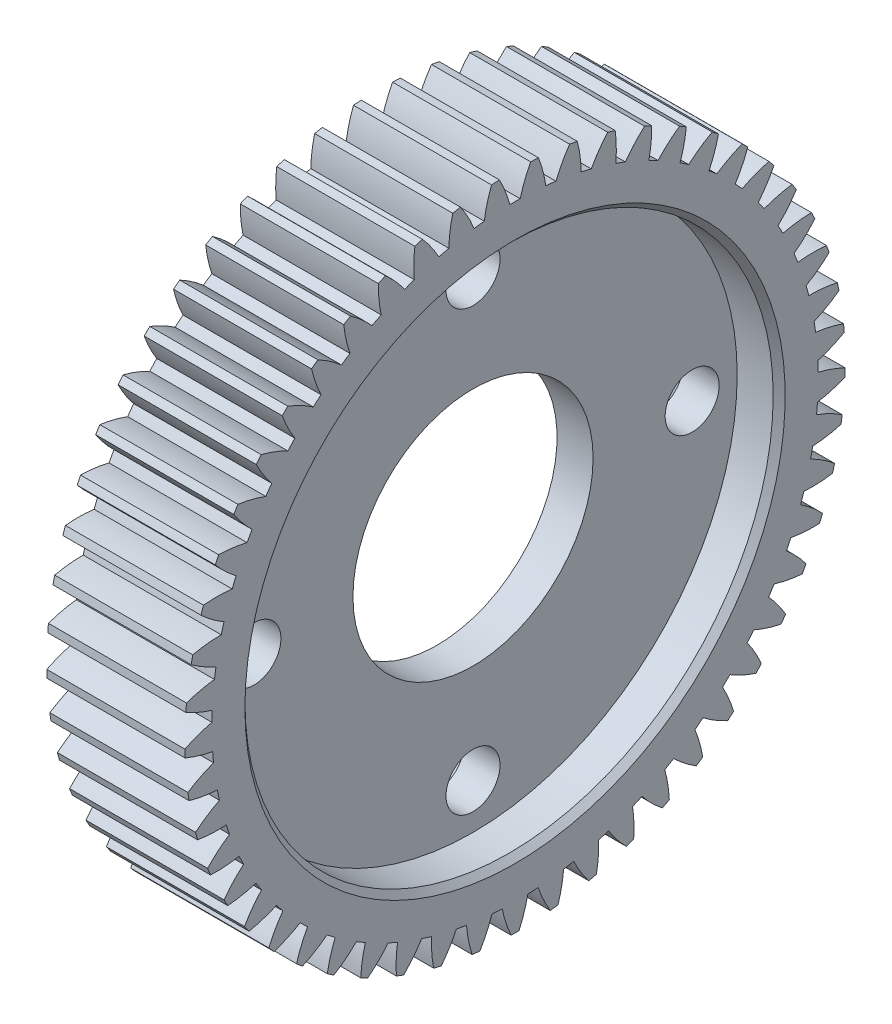
SolidWorks part; units mm, degrees
material "Plain Carbon Steel"
ref_plane "Plane1" through (0, 0, 0) normal (0, 0, 1) x (1, 0, 0)
ref_plane "Plane2" through (0, 0, 0) normal (0, 1, 0) x (1, 0, 0)
ref_plane "Plane3" through (0, 0, 0) normal (1, 0, 0) x (0, 0, -1)
sketch "HoldingSke" plane through (0, 0, 0) normal (0, 1, 0) x (1, 0, 0)
  line L0 (0, 0) -> (0.3009, -0.3993)
  line L1 (-15, 0) -> (100, 0) construction
  line L2 (0, 0) -> (-2.1039, 2.3779)
  line L3 (0, 0) -> (-11.863, 4.5341)
  line L4 (0, 0) -> (5.1973, 6.897)
  line L5 (0, 0) -> (-46.8476, -17.4728)
  line L6 (0, 0) -> (-19.0661, -12.864)
  line L7 (-2.1039, 2.3779) -> (8.6586, 51.2059)
  line L8 (-76.2, 54.61) -> (-72.9, 54.61)
  line L9 (-71.009, 38.7566) -> (-53.1078, 45.2721)
  line L10 (-76.2, 71.12) -> (104.1128, 71.12)
  line L11 (0, 0) -> (-23, 0)
  line L12 (-76.2, 101.6) -> (-76.133, 101.6)
  line L13 (24.9733, 27.94) -> (52.9518, 28.4284)
  line L14 (24.9733, 27.94) -> (24.9743, 27.94)
  line L15 (24.9733, 27.94) -> (100.4006, 29.5858)
  line L16 (-63.627, -2) -> (-12.827, -2)
  circle A0 centre (0, 0) radius 20
  circle A1 centre (0, 0) radius 37.5
  circle A2 centre (0, 0) radius 37.5
  circle A3 centre (0, 0) radius 20
  dimension "MHD" = 75
  dimension "Hub_dia" = 75
  dimension "Bore" = 40
  dimension "MBD" = 40
  dimension "Num_teeth" = 53
  dimension "Pitch" = 0.5
  dimension "Overall_len" = 50
  dimension "Show_teeth" = 53
  dimension "Thickness" = 23
  dimension "OAL" = 50.0001
  dimension "T_dim" = 3.3
  dimension "Ap" = 20
  dimension "H" = 19.05
  dimension "Pitch_radius" = 180.3128
  dimension "Width" = 23
  dimension "Backlash" = 0.067
  dimension "Addendum_fac" = 1
  dimension "Dedendum_fac" = 1.25
  dimension "Clearance_fac" = 0.25
  dimension "Dedendum_add" = 0.001
  dimension "Module" = 2
sketch "BasProSke" plane through (0, 0, 0) normal (0, 1, 0) x (1, 0, 0)
  line L0 (-10, 0) -> (60, 0) construction
  line L1 (0, 0) -> (0, 55)
  line L2 (0, 0) -> (23, 0)
  line L3 (23, 0) -> (23, 55)
  line L4 (23, 55) -> (0, 55)
  dimension "Thickness" = 23
  dimension "Diameter" = 110
revolve "Base-Revolve" add sketch "BasProSke" angle 360 about L0
sketch "TooCutSke" plane through (0, 0, 0) normal (1, 0, 0) x (0, 0, -1)
  line L1 (0, 0) -> (0, 107) construction
  line L2 (0, 0) -> (-1.6878, 52.9731) construction
  line L3 (0, 0) -> (-6.2771, 105.774) construction
  line L4 (-1.6878, 52.9731) -> (-3.1386, 52.887) construction
  arc A0 (0.8555, 50.4918) -> (-0.8555, 50.4918) centre (0, 0) ccw
  arc A1 (2.6179, 54.9631) -> (-2.6179, 54.9631) centre (0, 0) ccw
  circle A2 centre (0, 0) radius 53 construction
  circle A3 centre (0, 0) radius 49.8037 construction
  arc A4 (-0.8555, 50.4918) -> (-2.6179, 54.9631) centre (-21.3328, 45.0036) ccw
  arc A5 (2.6179, 54.9631) -> (0.8555, 50.4918) centre (21.3328, 45.0036) ccw
  dimension "Root_dia" = 100.998
  dimension "Overcut_dia" = 110.0508
  dimension "Pitch_dia" = 106
  dimension "Base_dia" = 99.6074
  dimension "Flank_rad" = 21.2
  dimension "Half_ang" = 3.396
  dimension "Half_CT" = 1.4533
extrude "ToothCut" cut sketch "TooCutSke" along normal through all
fillet "Breaks" [suppressed] radius 0.04
fillet "RootFillets" [suppressed] radius 0.501
pattern_circular "TeethCuts" count 53 every 6.792 about axis through (-10, 0, 0) along (1, 0, 0) of "ToothCut", "RootFillets", "Breaks"
sketch "HubNeaOneSke" plane through (0, 0, 0) normal (-1, 0, 0) x (0, 0, 1)
  circle A0 centre (0, 0) radius 37.5
  dimension "Diameter" = 75
extrude "HubNearOne" [suppressed] add sketch "HubNeaOneSke" along normal blind 27.0001
sketch "HubNeaBotSke" plane through (0, 0, 0) normal (-1, 0, 0) x (0, 0, 1)
  circle A0 centre (0, 0) radius 37.5
  dimension "Diameter" = 75
extrude "HubNearBoth" [suppressed] add sketch "HubNeaBotSke" along normal blind 13.5
ref_plane "FarPln" through (23, 0, 0) normal (1, 0, 0) x (0, 0, -1)
sketch "HubFarSke" plane through (23, 0, 0) normal (1, 0, 0) x (0, 0, -1)
  circle A0 centre (0, 0) radius 37.5
  dimension "Diameter" = 75
extrude "HubFar" [suppressed] add sketch "HubFarSke" along normal blind 13.5
sketch "BorSke" plane through (0, 0, 0) normal (1, 0, 0) x (0, 0, -1)
  circle A0 centre (0, 0) radius 20
  dimension "Diameter" = 40
extrude "Bore" cut sketch "BorSke" along normal mid plane 100.0001
sketch "KeySke" plane through (0, 0, 0) normal (1, 0, 0) x (0, 0, -1)
  line L0 (-6, 0) -> (-6, 23.3)
  line L1 (-6, 23.3) -> (6, 23.3)
  line L2 (6, 23.3) -> (6, 0)
  line L3 (0, 0) -> (0, 34) construction
  line L4 (-6, 0) -> (6, 0)
  dimension "Offset" = 23.3
  dimension "Width" = 12
extrude "Keyway" [suppressed] cut sketch "KeySke" along normal mid plane 100.0001
pattern_circular "Keyway2" [suppressed] count 2 every 90 about axis through (-10, 0, 0) along (1, 0, 0)
sketch "Sketch1" plane through (23, 0, 0) normal (1, 0, 0) x (0, 0, -1)
  circle A0 centre (0, 0) radius 44
  dimension "D1" = 88
extrude "Cut-Extrude1" cut sketch "Sketch1" against normal blind 7
chamfer "Chamfer1" distance 1 angle 45 1 edges at (23, 0, -44)
sketch "Sketch2" plane through (0, 0, 0) normal (-1, 0, 0) x (0, 0, 1)
  circle A0 centre (0, 0) radius 48
  dimension "D1" = 96
extrude "Cut-Extrude2" cut sketch "Sketch2" against normal blind 10
fillet "Fillet1" radius 2 1 edges at (10, 0, 48)
sketch "Sketch3" plane through (10, 0, 0) normal (-1, 0, 0) x (0, 0, 1)
  circle A0 centre (0, 0) radius 36.5 construction
  point P3 (0, 36.5)
  dimension "D1" = 73
hole_wizard "Ø9.0 (9) Diameter Hole1" positions "Sketch4" profile "Sketch5" hole size "Ø9.0" standard "ISO" end condition through all
sketch "Sketch4" plane through (10, 0, 0) normal (-1, 0, 0) x (0, 0, 1)
  point P0 (0, 36.5)
sketch "Sketch5" plane through (10, 36.5, 0) normal (0, 1, 0) x (0, 0, 1)
  line L0 (0, 0) -> (0, 13)
  line L1 (0, 13) -> (4.5, 13)
  line L2 (4.5, 13) -> (4.5, 0)
  line L5 (4.5, 0) -> (0, 0)
  line L11 (0, -6.35) -> (0, 107.95) construction
  dimension "Thru Hole Dia." = 9
  dimension "Thru Hole Depth" = 13
pattern_circular "CirPattern1" count 4 over 360 about axis through (0, 0, 0) along (1, 0, 0) of "Ø9.0 (9) Diameter Hole1"
equation "' \"Module@HoldingSke\" = 6.35"
equation "' \"Num_teeth@HoldingSke\" = 12"
equation "' \"Ap@HoldingSke\" =  20"
equation "' \"Ap@HoldingSke\" = 20"
equation "' \"Width@HoldingSke\" = 0.5 * 25.4"
equation "' \"Hub_dia@HoldingSke\"= 1 * 25.4"
equation "' \"Hub_dia@HoldingSke\" = 1 * 25.4"
equation "' \"Overall_len@HoldingSke\" = 1.0 * 25.4"
equation "' \"Bore@HoldingSke\" = 0.75 * 25.4"
equation "' \"T_dim@HoldingSke\" = 0.1 * 25.4"
equation "' \"Width@KeySke\" = 0.25 * 25.4"
equation "' \"Show_teeth@HoldingSke\" = 13"
equation "' \"Backlash@HoldingSke\" = 0.009 * 25.4"
equation "' \"Addendum_fac@HoldingSke\" = 1.0"
equation "' \"Dedendum_fac@HoldingSke\" = 1.25"
equation "' \"Dedendum_add@HoldingSke\" = 0.00005 * 25.4"
equation "' \"Clearance_fac@HoldingSke\" = 0.25"
equation "\"Pitch@HoldingSke\" = 1 / \"Module@HoldingSke\""
equation "\"Overcut_dia@TooCutSke\" = (\"Num_teeth@HoldingSke\" + 2 * \"Addendum_fac@HoldingSke\") / \"Pitch@HoldingSke\" + 0.002 * 25.4"
equation "\"Pitch_dia@TooCutSke\" = \"Num_teeth@HoldingSke\" / \"Pitch@HoldingSke\""
equation "\"Base_dia@TooCutSke\" = \"Num_teeth@HoldingSke\" / \"Pitch@HoldingSke\" * cos((\"Ap@HoldingSke\"  * 3.14159265 / 180))"
equation "\"Root_dia@TooCutSke\" = (\"Num_teeth@HoldingSke\" + 2) / \"Pitch@HoldingSke\" - 2 * (\"Addendum_fac@HoldingSke\" + \"Dedendum_fac@HoldingSke\") / \"Pitch@HoldingSke\" - \"Dedendum_add@HoldingSke\" * 2"
equation "\"Half_ang@TooCutSke\" = 180 / \"Num_teeth@HoldingSke\""
equation "\"Half_CT@TooCutSke\" = \"Num_teeth@HoldingSke\" / \"Pitch@HoldingSke\" * sin((3.14159265 / 2 / \"Num_teeth@HoldingSke\")) / 2 - 7 * \"Backlash@HoldingSke\" / 4"
equation "\"Flank_rad@TooCutSke\" = \"Num_teeth@HoldingSke\" / \"Pitch@HoldingSke\" / 5"
equation "\"Radius@RootFillets\" = \"Clearance_fac@HoldingSke\" / \"Pitch@HoldingSke\" + \"Dedendum_add@HoldingSke\""
equation "\"Break_rad@Breaks\" = 0.02 / \"Pitch@HoldingSke\""
equation "\"Thickness@HoldingSke\" = \"Width@HoldingSke\""
equation "\"OAL@HoldingSke\" = \"Thickness@HoldingSke\""
equation "\"MHD@HoldingSke\" = (\"Num_teeth@HoldingSke\" + 2) / \"Pitch@HoldingSke\" - 2 * (\"Addendum_fac@HoldingSke\" + \"Dedendum_fac@HoldingSke\")  / \"Pitch@HoldingSke\" - \"Dedendum_add@HoldingSke\" * 2"
equation "\"MBD@HoldingSke\" = (\"Num_teeth@HoldingSke\" + 2) / \"Pitch@HoldingSke\" - 2 * (\"Addendum_fac@HoldingSke\" + \"Dedendum_fac@HoldingSke\")  / \"Pitch@HoldingSke\" - \"Dedendum_add@HoldingSke\" * 2 - 0.002 * 25.4"
equation "\"MHD@HoldingSke\" = ((sgn( \"MHD@HoldingSke\" - \"Hub_dia@HoldingSke\" )-1)*( \"MHD@HoldingSke\" - \"Hub_dia@HoldingSke\" ))/-2+ \"Hub_dia@HoldingSke\""
equation "\"MBD@HoldingSke\" = ((sgn( \"MBD@HoldingSke\" - \"Bore@HoldingSke\" )-1)*( \"MBD@HoldingSke\" - \"Bore@HoldingSke\" ))/-2+ \"Bore@HoldingSke\""
equation "\"OAL@HoldingSke\" = ((sgn( \"OAL@HoldingSke\" - \"Overall_len@HoldingSke\" )+1)*( \"OAL@HoldingSke\" - \"Overall_len@HoldingSke\" ))/2 + \"Overall_len@HoldingSke\" + 0.000002 * 25.4"
equation "\"Num_teeth@TeethCuts\" = int( \"Show_teeth@HoldingSke\" ) + 1"
equation "\"Num_teeth@TeethCuts\" = ((sgn( \"Num_teeth@TeethCuts\" - \"Num_teeth@HoldingSke\" )-1)*( \"Num_teeth@TeethCuts\" - \"Num_teeth@HoldingSke\" ))/-2+ \"Num_teeth@HoldingSke\""
equation "\"Num_teeth@TeethCuts\" = ((sgn( \"Num_teeth@TeethCuts\" - 2.0)+1)*( \"Num_teeth@TeethCuts\" - 2.0))/2 +2.0"
equation "\"Angle@TeethCuts\" = 360.0 / \"Num_teeth@HoldingSke\""
equation "\"Diameter@BasProSke\" = (\"Num_teeth@HoldingSke\" + 2 * \"Addendum_fac@HoldingSke\") / \"Pitch@HoldingSke\""
equation "\"Thickness@BasProSke\"  = \"Thickness@HoldingSke\""
equation "' \"Fillet_rad@BasProSke\" =  \"Thickness@HoldingSke\" * 0.05"
equation "' \"Fillet_rad@BasProSke\" = \"Thickness@HoldingSke\" * 0.05"
equation "\"MHD@HoldingSke\" = ((sgn( \"MHD@HoldingSke\" - \"Root_dia@TooCutSke\" )-1)*( \"MHD@HoldingSke\" - \"Root_dia@TooCutSke\" ))/-2+ \"Root_dia@TooCutSke\""
equation "\"Diameter@HubNeaOneSke\" = \"MHD@HoldingSke\""
equation "\"Length@HubNearOne\" = \"OAL@HoldingSke\" - \"Thickness@BasProSke\""
equation "\"Diameter@HubNeaBotSke\" = \"MHD@HoldingSke\""
equation "\"Length@HubNearBoth\" = ( \"OAL@HoldingSke\" - \"Thickness@BasProSke\" ) / 2.0"
equation "\"Thickness@FarPln\" = \"Thickness@BasProSke\""
equation "\"Diameter@HubFarSke\" = \"MHD@HoldingSke\""
equation "\"Length@HubFar\" = ( \"OAL@HoldingSke\" - \"Thickness@BasProSke\" ) / 2.0"
equation "\"Diameter@BorSke\" = \"MBD@HoldingSke\""
equation "\"D1@Bore\" = \"OAL@HoldingSke\" * 2.0"
equation "\"D1@Keyway\" = \"OAL@HoldingSke\" * 2.0"
equation "\"Offset@KeySke\" = \"T_dim@HoldingSke\" + \"MBD@HoldingSke\" / 2.0"
